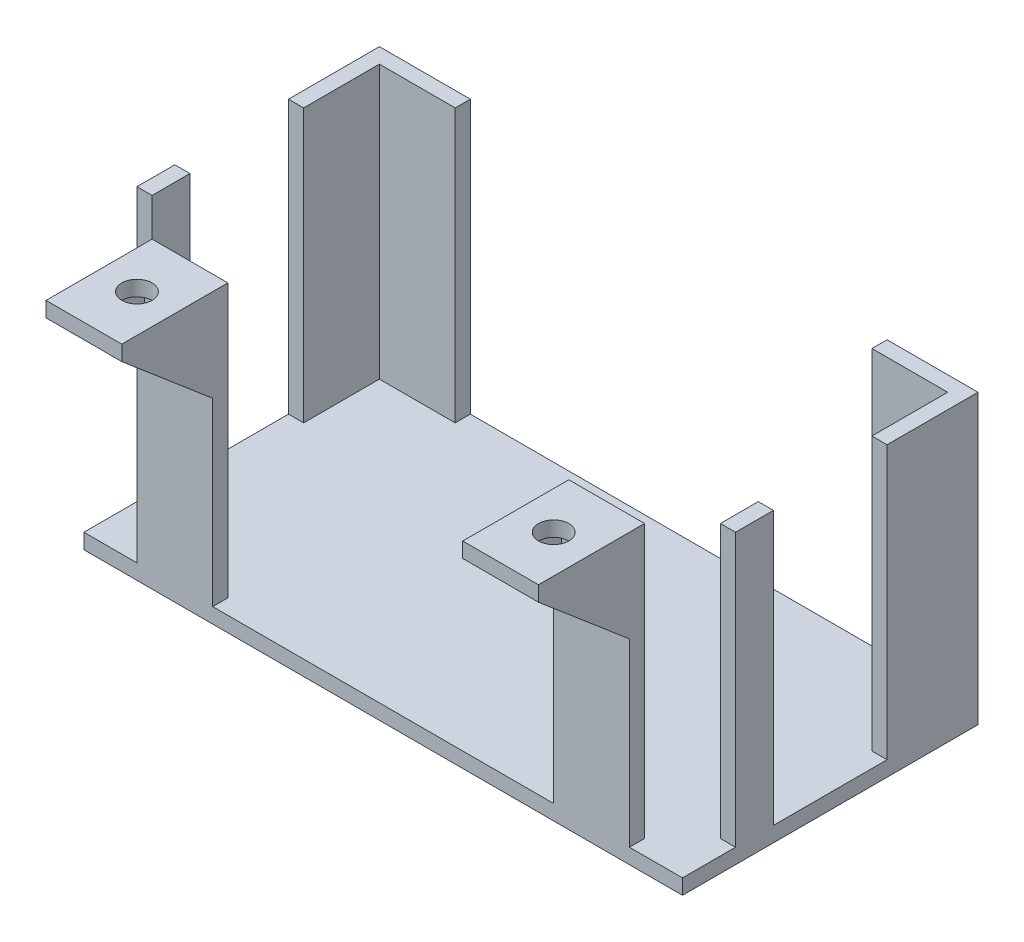
SolidWorks part; units mm, degrees
ref_plane "Alzado" through (0, 0, 0) normal (0, 0, 1) x (1, 0, 0)
ref_plane "Planta" through (0, 0, 0) normal (0, 1, 0) x (1, 0, 0)
ref_plane "Vista lateral" through (0, 0, 0) normal (1, 0, 0) x (0, 0, -1)
sketch "Croquis1" plane through (0, 0, 0) normal (0, 1, 0) x (1, 0, 0)
  line L0 (-39.5, 7.5) -> (-37.5, 7.5)
  line L1 (-39.5, 19.5) -> (39.5, 19.5)
  line L2 (-39.5, 19.5) -> (-39.5, -19.5)
  line L3 (-39.5, -19.5) -> (39.5, -19.5)
  line L4 (39.5, 19.5) -> (39.5, -19.5)
  line L5 (-39.5, 19.5) -> (39.5, -19.5) construction
  line L6 (-39.5, -19.5) -> (39.5, 19.5) construction
  line L7 (-37.5, 7.5) -> (-37.5, 17.5)
  line L8 (-37.5, 17.5) -> (-27.5, 17.5)
  line L9 (-27.5, 17.5) -> (-27.5, 19.5)
  line L10 (0, 31.4083) -> (0, -25.473) construction
  line L11 (-39.5, -7.5) -> (-37.5, -7.5)
  line L12 (-37.5, -7.5) -> (-37.5, -17.5)
  line L13 (-37.5, -17.5) -> (-27.5, -17.5)
  line L14 (-27.5, -17.5) -> (-27.5, -19.5)
  line L15 (-27.5, 19.5) -> (-39.5, 19.5)
  line L16 (-39.5, 7.5) -> (-39.5, 19.5)
  line L17 (-39.5, -7.5) -> (-39.5, -19.5)
  line L18 (-39.5, -19.5) -> (-27.5, -19.5)
  line L19 (39.5, -7.5) -> (39.5, -19.5)
  line L20 (39.5, -19.5) -> (27.5, -19.5)
  line L21 (27.5, -17.5) -> (27.5, -19.5)
  line L22 (37.5, -17.5) -> (27.5, -17.5)
  line L23 (37.5, -7.5) -> (37.5, -17.5)
  line L24 (39.5, -7.5) -> (37.5, -7.5)
  line L25 (27.5, 17.5) -> (27.5, 19.5)
  line L26 (39.5, 7.5) -> (39.5, 19.5)
  line L27 (27.5, 19.5) -> (39.5, 19.5)
  line L28 (37.5, 7.5) -> (37.5, 17.5)
  line L29 (39.5, 7.5) -> (37.5, 7.5)
  line L30 (37.5, 17.5) -> (27.5, 17.5)
  line L31 (37.5, -12.5) -> (39.5, -12.5)
  line L32 (32.5, -17.5) -> (32.5, -19.5)
  point P0 (0, 0)
  point P17 (-27.5, 18.5)
  dimension "D1" = 39
  dimension "D2" = 79
  dimension "D3" = 2
  dimension "D4" = 2
  dimension "D5" = 2
  dimension "D6" = 2
  dimension "D7" = 12
  dimension "D8" = 12
  dimension "D9" = 12
  dimension "D10" = 12
extrude "Saliente-Extruir1" add sketch "Croquis1" along normal blind 36 contours L32 L22 L21 L3 | L23 L31 L4 L24 | L30 L28 L29 L4 L1 L25 | L16 L0 L7 L8 L9 L15 | L17 L11 L12 L13 L14 L18
sketch "Croquis2" plane through (0, 0, 0) normal (0, -1, 0) x (1, 0, 0)
  line L1 (39.5, -19.5) -> (-39.5, -19.5)
  line L2 (39.5, -19.5) -> (39.5, 19.5)
  line L3 (39.5, 19.5) -> (-39.5, 19.5)
  line L4 (-39.5, -19.5) -> (-39.5, 19.5)
extrude "Saliente-Extruir2" add sketch "Croquis2" along normal blind 2
sketch "Croquis3" plane through (0, 36, 0) normal (0, 1, 0) x (1, 0, 0)
  line L0 (-32.5, -17.5) -> (-32.5, -19.5)
  line L1 (-37.5, -17.5) -> (-27.5, -17.5) construction
  line L2 (-39.5, -19.5) -> (-27.5, -19.5) construction
  line L3 (-32.5, -17.5) -> (-37.5, -17.5)
  line L4 (-37.5, -17.5) -> (-37.5, -12.5)
  line L5 (-37.5, -7.5) -> (-37.5, -17.5) construction
  line L6 (-37.5, -12.5) -> (-39.5, -12.5)
  line L7 (-39.5, -7.5) -> (-39.5, -19.5) construction
  line L8 (-39.5, -12.5) -> (-39.5, -19.5)
  line L9 (-39.5, -19.5) -> (-32.5, -19.5)
extrude "Cortar-Extruir1" cut sketch "Croquis3" against normal up to surface (36 mm away) up to face at (6, 0, 2.6667)
sketch "Croquis4" plane through (0, 0, 0) normal (0, 1, 0) x (1, 0, 0)
  line L0 (27.5, -19.5) -> (-27.5, -19.5) construction
  line L1 (-22.5, -19.5) -> (-27.5, -19.5)
  line L2 (-22.5, -19.5) -> (-22.5, -17.5)
  line L3 (-22.5, -17.5) -> (-27.5, -17.5)
  line L4 (-27.5, -19.5) -> (-27.5, -17.5)
  line L5 (0, 0) -> (0, -28.9649) construction
  line L6 (-32.5, -19.5) -> (-32.5, -17.5) construction
  line L7 (22.5, -17.5) -> (27.5, -17.5)
  line L8 (27.5, -19.5) -> (27.5, -17.5)
  line L9 (22.5, -19.5) -> (27.5, -19.5)
  line L10 (22.5, -19.5) -> (22.5, -17.5)
  dimension "D1" = 10
extrude "Saliente-Extruir3" add sketch "Croquis4" along normal up to surface (36 mm away) up to face at (-30, 36, 18.5)
sketch "Croquis5" plane through (0, 0, 19.5) normal (0, 0, 1) x (1, 0, 0)
  line L6 (-32.5, 0) -> (-32.5, 36) construction
  line L7 (-22.5, 36) -> (-32.5, 36)
  line L8 (-22.5, 36) -> (-22.5, 34)
  line L9 (-22.5, 34) -> (-32.5, 34)
  line L10 (-32.5, 36) -> (-32.5, 34)
  line L11 (0, -2) -> (0, 40.5687) construction
  line L12 (39.5, -2) -> (-39.5, -2) construction
  line L13 (22.5, 34) -> (32.5, 34)
  line L14 (32.5, 36) -> (32.5, 34)
  line L15 (22.5, 36) -> (32.5, 36)
  line L16 (22.5, 36) -> (22.5, 34)
  dimension "D1" = 2
extrude "Saliente-Extruir4" add sketch "Croquis5" along normal blind 12
sketch "Croquis8" plane through (-32.5, 0, 0) normal (-1, 0, 0) x (0, 0, 1)
  line L0 (31.5, 34) -> (19.5, 23.8103)
  line L1 (19.5, 0) -> (19.5, 34) construction
  line L2 (31.5, 34) -> (19.5, 34) construction
  dimension "D1" = 10.1897
rib "Nervio1" sketch "Croquis8" sketch "Croquis8" thickness 1 extrusion direction parallel to sketch draft on no parameters "D1"=1
sketch "Croquis9" plane through (-22.5, 0, 0) normal (1, 0, 0) x (0, 0, -1)
  line L0 (-31.5, 34) -> (-19.5, 23.8103)
rib "Nervio2" sketch "Croquis9" sketch "Croquis9" thickness 1 extrusion direction parallel to sketch draft on no parameters "D1"=1
sketch "Croquis10" plane through (32.5, 0, 0) normal (1, 0, 0) x (0, 0, -1)
  line L0 (-31.5, 34) -> (-19.5, 23.8103)
rib "Nervio3" sketch "Croquis10" sketch "Croquis10" thickness 1 extrusion direction parallel to sketch draft on no parameters "D1"=1
sketch "Croquis11" plane through (22.5, 0, 0) normal (-1, 0, 0) x (0, 0, 1)
  line L0 (19.5, 23.8103) -> (31.5, 34)
rib "Nervio4" sketch "Croquis11" sketch "Croquis11" thickness 1 extrusion direction parallel to sketch draft on no parameters "D1"=1
sketch "Croquis12" plane through (0, 36, 0) normal (0, 1, 0) x (1, 0, 0)
  line L0 (32.5, -24.5) -> (22.5, -24.5) construction
  line L1 (32.5, -17.5) -> (32.5, -31.5) construction
  line L2 (22.5, -31.5) -> (22.5, -17.5) construction
  line L3 (-22.5, -24.5) -> (-32.5, -24.5) construction
  line L4 (-22.5, -17.5) -> (-22.5, -31.5) construction
  line L5 (-32.5, -31.5) -> (-32.5, -17.5) construction
  circle A0 centre (27.5, -24.5) radius 2
  circle A1 centre (-27.5, -24.5) radius 2
  dimension "D1" = 4
extrude "Cortar-Extruir2" cut sketch "Croquis12" against normal through all
